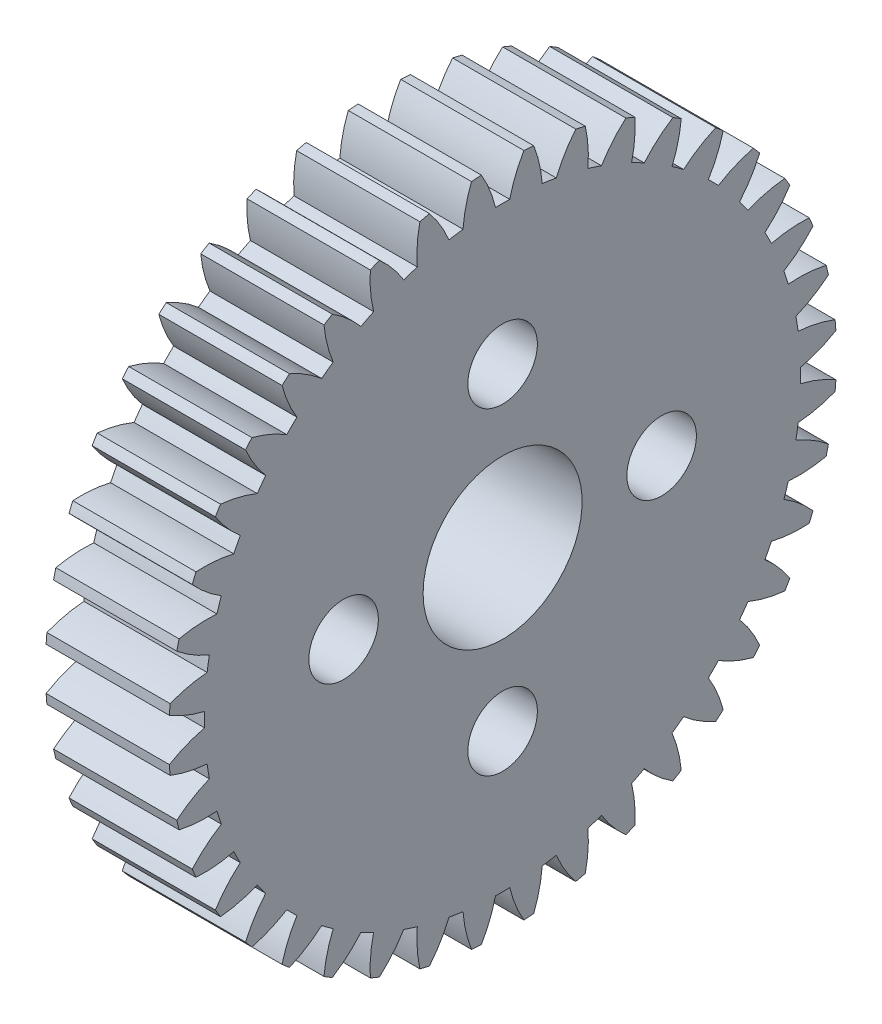
SolidWorks part; units mm, degrees
other "Defeature"
material "6061 Alloy"
ref_plane "Plane1" through (0, 0, 0) normal (0, 0, 1) x (1, 0, 0)
ref_plane "Plane2" through (0, 0, 0) normal (0, 1, 0) x (1, 0, 0)
ref_plane "Plane3" through (0, 0, 0) normal (1, 0, 0) x (0, 0, -1)
sketch "HoldingSke" plane through (0, 0, 0) normal (0, 1, 0) x (1, 0, 0)
  line L0 (0, 0) -> (0.9576, -0.8035)
  line L1 (-15, 0) -> (100, 0) construction
  line L2 (0, 0) -> (-2.1039, 2.3779)
  line L3 (0, 0) -> (-11.863, 4.5341)
  line L4 (0, 0) -> (6.6156, 5.5511)
  line L5 (0, 0) -> (-46.8476, -17.4728)
  line L6 (0, 0) -> (-5.1396, -3.4677)
  line L7 (-2.1039, 2.3779) -> (8.6586, 51.2059)
  line L8 (-76.2, 54.61) -> (-74.8, 54.61)
  line L9 (-71.009, 38.7566) -> (-53.1078, 45.2721)
  line L10 (-76.2, 71.12) -> (104.1128, 71.12)
  line L11 (0, 0) -> (-6.2, 0)
  line L12 (-76.2, 101.6) -> (-76.17, 101.6)
  line L13 (24.9733, 27.94) -> (52.9518, 28.4284)
  line L14 (24.9733, 27.94) -> (24.9743, 27.94)
  line L15 (24.9733, 27.94) -> (100.4006, 29.5858)
  line L16 (-63.627, -0.8) -> (-12.827, -0.8)
  circle A0 centre (0, 0) radius 4
  circle A1 centre (0, 0) radius 14.999
  circle A2 centre (0, 0) radius 37.5
  circle A3 centre (0, 0) radius 4
  dimension "MHD" = 29.998
  dimension "Hub_dia" = 75
  dimension "Bore" = 8
  dimension "MBD" = 8
  dimension "Num_teeth" = 40
  dimension "Pitch_radius" = 180.3128
  dimension "Pitch" = 1.25
  dimension "Width" = 6.2
  dimension "Overall_len" = 50
  dimension "Show_teeth" = 40
  dimension "Thickness" = 6.2
  dimension "OAL" = 50.0001
  dimension "T_dim" = 1.4
  dimension "Ap" = 20
  dimension "H" = 19.05
  dimension "Backlash" = 0.03
  dimension "Addendum_fac" = 1
  dimension "Dedendum_fac" = 1.25
  dimension "Clearance_fac" = 0.25
  dimension "Dedendum_add" = 0.001
  dimension "Module" = 0.8
sketch "BasProSke" plane through (0, 0, 0) normal (0, 1, 0) x (1, 0, 0)
  line L0 (-10, 0) -> (60, 0) construction
  line L1 (0, 0) -> (0, 16.8)
  line L2 (0, 0) -> (6.2, 0)
  line L3 (6.2, 0) -> (6.2, 16.8)
  line L4 (6.2, 16.8) -> (0, 16.8)
  dimension "Diameter" = 33.6
  dimension "Thickness" = 6.2
revolve "Base-Revolve" add sketch "BasProSke" angle 360 about L0
sketch "TooCutSke" plane through (0, 0, 0) normal (1, 0, 0) x (0, 0, -1)
  line L1 (0, 0) -> (0, 107) construction
  line L2 (0, 0) -> (-0.6807, 15.9855) construction
  line L3 (0, 0) -> (-2.5091, 31.8807) construction
  line L4 (-0.6807, 15.9855) -> (-1.2545, 15.9404) construction
  arc A0 (0.3582, 14.9947) -> (-0.3582, 14.9947) centre (0, 0) ccw
  arc A1 (1.086, 16.7903) -> (-1.086, 16.7903) centre (0, 0) ccw
  circle A2 centre (0, 0) radius 16 construction
  circle A3 centre (0, 0) radius 15.0351 construction
  arc A4 (-0.3582, 14.9947) -> (-1.086, 16.7903) centre (-6.5851, 13.5163) ccw
  arc A5 (1.086, 16.7903) -> (0.3582, 14.9947) centre (6.5851, 13.5163) ccw
  dimension "Root_dia" = 29.998
  dimension "Overcut_dia" = 33.6508
  dimension "Pitch_dia" = 32
  dimension "Base_dia" = 30.0702
  dimension "Flank_rad" = 6.4
  dimension "Half_ang" = 4.5
  dimension "Half_CT" = 0.5757
extrude "ToothCut" cut sketch "TooCutSke" along normal through all
fillet "Breaks" [suppressed] radius 0.016
fillet "RootFillets" [suppressed] radius 0.201
pattern_circular "TeethCuts" count 40 over 360 about axis through (0, 0, 0) along (1, 0, 0) of "ToothCut", "RootFillets", "Breaks"
sketch "HubNeaOneSke" plane through (0, 0, 0) normal (-1, 0, 0) x (0, 0, 1)
  circle A0 centre (0, 0) radius 14.999
  dimension "Diameter" = 29.998
extrude "HubNearOne" [suppressed] add sketch "HubNeaOneSke" along normal blind 43.8001
sketch "HubNeaBotSke" plane through (0, 0, 0) normal (-1, 0, 0) x (0, 0, 1)
  circle A0 centre (0, 0) radius 14.999
  dimension "Diameter" = 29.998
extrude "HubNearBoth" [suppressed] add sketch "HubNeaBotSke" along normal blind 21.9
ref_plane "FarPln" through (6.2, 0, 0) normal (1, 0, 0) x (0, 0, -1)
sketch "HubFarSke" plane through (6.2, 0, 0) normal (1, 0, 0) x (0, 0, -1)
  circle A0 centre (0, 0) radius 14.999
  dimension "Diameter" = 29.998
extrude "HubFar" [suppressed] add sketch "HubFarSke" along normal blind 21.9
sketch "BorSke" plane through (0, 0, 0) normal (1, 0, 0) x (0, 0, -1)
  circle A0 centre (0, 0) radius 4
  dimension "Diameter" = 8
extrude "Bore" cut sketch "BorSke" along normal mid plane 100.0001
sketch "KeySke" plane through (0, 0, 0) normal (1, 0, 0) x (0, 0, -1)
  line L0 (-1.5, 0) -> (-1.5, 5.4)
  line L1 (-1.5, 5.4) -> (1.5, 5.4)
  line L2 (1.5, 5.4) -> (1.5, 0)
  line L3 (0, 0) -> (0, 34) construction
  line L4 (-1.5, 0) -> (1.5, 0)
  dimension "Offset" = 5.4
  dimension "Width" = 3
extrude "Keyway" [suppressed] cut sketch "KeySke" along normal mid plane 100.0001
pattern_circular "Keyway2" [suppressed] count 2 every 90 about axis through (-10, 0, 0) along (1, 0, 0)
sketch "Sketch1" plane through (6.2, 0, 0) normal (1, 0, 0) x (0, 0, -1)
  circle A0 centre (0, 8) radius 1.75
  circle A1 centre (0, -8) radius 1.75
  circle A2 centre (8, 0) radius 1.75
  circle A3 centre (-8, 0) radius 1.75
  circle A4 centre (0, 0) radius 8 construction
  dimension "D1" = 3.5
  dimension "D2" = 16
extrude "Cut-Extrude1" cut sketch "Sketch1" against normal through all
equation "' \"Module@HoldingSke\" = 6.35"
equation "' \"Num_teeth@HoldingSke\" = 12"
equation "' \"Ap@HoldingSke\" =  20"
equation "' \"Width@HoldingSke\" = 0.5 * 25.4"
equation "' \"Hub_dia@HoldingSke\"= 1 * 25.4"
equation "' \"Overall_len@HoldingSke\" = 1.0 * 25.4"
equation "' \"Bore@HoldingSke\" = 0.75 * 25.4"
equation "' \"T_dim@HoldingSke\" = 0.1 * 25.4"
equation "' \"Width@KeySke\" = 0.25 * 25.4"
equation "' \"Show_teeth@HoldingSke\" = 13"
equation "' \"Backlash@HoldingSke\" = 0.009 * 25.4"
equation "' \"Addendum_fac@HoldingSke\" = 1.0"
equation "' \"Dedendum_fac@HoldingSke\" = 1.25"
equation "' \"Dedendum_add@HoldingSke\" = 0.00005 * 25.4"
equation "' \"Clearance_fac@HoldingSke\" = 0.25"
equation "\"Pitch@HoldingSke\" = 1 / \"Module@HoldingSke\""
equation "\"Overcut_dia@TooCutSke\" = (\"Num_teeth@HoldingSke\" + 2 * \"Addendum_fac@HoldingSke\") / \"Pitch@HoldingSke\" + 0.002 * 25.4"
equation "\"Pitch_dia@TooCutSke\" = \"Num_teeth@HoldingSke\" / \"Pitch@HoldingSke\""
equation "\"Base_dia@TooCutSke\" = \"Num_teeth@HoldingSke\" / \"Pitch@HoldingSke\" * cos((\"Ap@HoldingSke\"  * 3.14159265 / 180))"
equation "\"Root_dia@TooCutSke\" = (\"Num_teeth@HoldingSke\" + 2) / \"Pitch@HoldingSke\" - 2 * (\"Addendum_fac@HoldingSke\" + \"Dedendum_fac@HoldingSke\") / \"Pitch@HoldingSke\" - \"Dedendum_add@HoldingSke\" * 2"
equation "\"Half_ang@TooCutSke\" = 180 / \"Num_teeth@HoldingSke\""
equation "\"Half_CT@TooCutSke\" = \"Num_teeth@HoldingSke\" / \"Pitch@HoldingSke\" * sin((3.14159265 / 2 / \"Num_teeth@HoldingSke\")) / 2 - 7 * \"Backlash@HoldingSke\" / 4"
equation "\"Flank_rad@TooCutSke\" = \"Num_teeth@HoldingSke\" / \"Pitch@HoldingSke\" / 5"
equation "\"Radius@RootFillets\" = \"Clearance_fac@HoldingSke\" / \"Pitch@HoldingSke\" + \"Dedendum_add@HoldingSke\""
equation "\"Break_rad@Breaks\" = 0.02 / \"Pitch@HoldingSke\""
equation "\"Thickness@HoldingSke\" = \"Width@HoldingSke\""
equation "\"OAL@HoldingSke\" = \"Thickness@HoldingSke\""
equation "\"MHD@HoldingSke\" = (\"Num_teeth@HoldingSke\" + 2) / \"Pitch@HoldingSke\" - 2 * (\"Addendum_fac@HoldingSke\" + \"Dedendum_fac@HoldingSke\")  / \"Pitch@HoldingSke\" - \"Dedendum_add@HoldingSke\" * 2"
equation "\"MBD@HoldingSke\" = (\"Num_teeth@HoldingSke\" + 2) / \"Pitch@HoldingSke\" - 2 * (\"Addendum_fac@HoldingSke\" + \"Dedendum_fac@HoldingSke\")  / \"Pitch@HoldingSke\" - \"Dedendum_add@HoldingSke\" * 2 - 0.002 * 25.4"
equation "\"MHD@HoldingSke\" = ((sgn( \"MHD@HoldingSke\" - \"Hub_dia@HoldingSke\" )-1)*( \"MHD@HoldingSke\" - \"Hub_dia@HoldingSke\" ))/-2+ \"Hub_dia@HoldingSke\""
equation "\"MBD@HoldingSke\" = ((sgn( \"MBD@HoldingSke\" - \"Bore@HoldingSke\" )-1)*( \"MBD@HoldingSke\" - \"Bore@HoldingSke\" ))/-2+ \"Bore@HoldingSke\""
equation "\"OAL@HoldingSke\" = ((sgn( \"OAL@HoldingSke\" - \"Overall_len@HoldingSke\" )+1)*( \"OAL@HoldingSke\" - \"Overall_len@HoldingSke\" ))/2 + \"Overall_len@HoldingSke\" + 0.000002 * 25.4"
equation "\"Num_teeth@TeethCuts\" = int( \"Show_teeth@HoldingSke\" ) + 1"
equation "\"Num_teeth@TeethCuts\" = ((sgn( \"Num_teeth@TeethCuts\" - \"Num_teeth@HoldingSke\" )-1)*( \"Num_teeth@TeethCuts\" - \"Num_teeth@HoldingSke\" ))/-2+ \"Num_teeth@HoldingSke\""
equation "\"Num_teeth@TeethCuts\" = ((sgn( \"Num_teeth@TeethCuts\" - 2.0)+1)*( \"Num_teeth@TeethCuts\" - 2.0))/2 +2.0"
equation "\"Angle@TeethCuts\" = 360.0 / \"Num_teeth@HoldingSke\""
equation "\"Diameter@BasProSke\" = (\"Num_teeth@HoldingSke\" + 2 * \"Addendum_fac@HoldingSke\") / \"Pitch@HoldingSke\""
equation "\"Thickness@BasProSke\"  = \"Thickness@HoldingSke\""
equation "' \"Fillet_rad@BasProSke\" =  \"Thickness@HoldingSke\" * 0.05"
equation "\"MHD@HoldingSke\" = ((sgn( \"MHD@HoldingSke\" - \"Root_dia@TooCutSke\" )-1)*( \"MHD@HoldingSke\" - \"Root_dia@TooCutSke\" ))/-2+ \"Root_dia@TooCutSke\""
equation "\"Diameter@HubNeaOneSke\" = \"MHD@HoldingSke\""
equation "\"Length@HubNearOne\" = \"OAL@HoldingSke\" - \"Thickness@BasProSke\""
equation "\"Diameter@HubNeaBotSke\" = \"MHD@HoldingSke\""
equation "\"Length@HubNearBoth\" = ( \"OAL@HoldingSke\" - \"Thickness@BasProSke\" ) / 2.0"
equation "\"Thickness@FarPln\" = \"Thickness@BasProSke\""
equation "\"Diameter@HubFarSke\" = \"MHD@HoldingSke\""
equation "\"Length@HubFar\" = ( \"OAL@HoldingSke\" - \"Thickness@BasProSke\" ) / 2.0"
equation "\"Diameter@BorSke\" = \"MBD@HoldingSke\""
equation "\"D1@Bore\" = \"OAL@HoldingSke\" * 2.0"
equation "\"D1@Keyway\" = \"OAL@HoldingSke\" * 2.0"
equation "\"Offset@KeySke\" = \"T_dim@HoldingSke\" + \"MBD@HoldingSke\" / 2.0"
